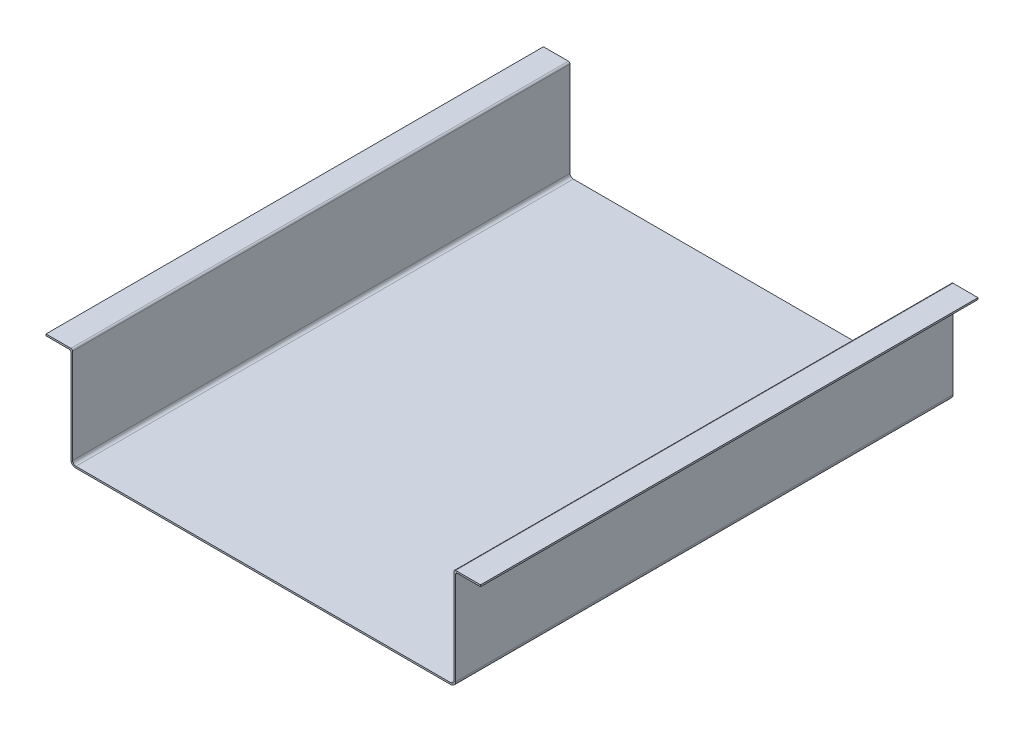
SolidWorks part; units mm, degrees
material "6061-T6 (SS)"
ref_plane "Front Plane" through (0, 0, 0) normal (0, 0, 1) x (1, 0, 0)
ref_plane "Top Plane" through (0, 0, 0) normal (0, 1, 0) x (1, 0, 0)
ref_plane "Right Plane" through (0, 0, 0) normal (1, 0, 0) x (0, 0, -1)
sketch "Sketch2" plane through (0, 0, 0) normal (0, 0, 1) x (1, 0, 0)
  line L0 (-179.1462, 0) -> (179.1462, 0)
  line L1 (-183.896, 4.7498) -> (-183.896, 93.6625)
  line L2 (-185.4835, 95.25) -> (-207.6958, 95.25)
  line L3 (-182.2958, 95.25) -> (-182.2958, 4.7625)
  line L4 (-179.1208, 1.5875) -> (179.1208, 1.5875)
  line L5 (182.2958, 4.7625) -> (182.2958, 95.2627)
  line L6 (185.4835, 95.25) -> (207.6958, 95.25)
  line L7 (183.896, 93.6625) -> (183.896, 4.7498)
  line L8 (0, 1.5875) -> (0, 0) construction
  line L9 (-207.6958, 95.25) -> (-207.6958, 96.8502)
  line L10 (-207.6958, 96.8502) -> (-183.8833, 96.8502)
  line L11 (-182.2958, 95.25) -> (-182.2958, 95.2627)
  line L12 (-182.2958, 94.3244) -> (-183.896, 94.3244) construction
  line L13 (207.6958, 95.25) -> (207.6958, 96.8502)
  line L14 (207.6958, 96.8502) -> (183.8833, 96.8502)
  line L16 (183.896, 90.4071) -> (182.2958, 90.4071) construction
  arc A0 (-182.2958, 4.7625) -> (-179.1208, 1.5875) centre (-179.1208, 4.7625) ccw
  arc A1 (-179.1462, 0) -> (-183.896, 4.7498) centre (-179.1462, 4.7498) cw
  arc A2 (179.1462, 0) -> (183.896, 4.7498) centre (179.1462, 4.7498) ccw
  arc A3 (179.1208, 1.5875) -> (182.2958, 4.7625) centre (179.1208, 4.7625) ccw
  arc A4 (-183.8833, 96.8502) -> (-182.2958, 95.2627) centre (-183.8833, 95.2627) cw
  arc A5 (-183.896, 93.6625) -> (-185.4835, 95.25) centre (-185.4835, 93.6625) ccw
  arc A6 (183.8833, 96.8502) -> (182.2958, 95.2627) centre (183.8833, 95.2627) ccw
  arc A7 (185.4835, 95.25) -> (183.896, 93.6625) centre (185.4835, 93.6625) ccw
  point P3 (0, 0)
  point P16 (-183.896, 0)
  point P19 (183.896, 0)
  point P31 (-183.896, 95.25)
  dimension "D4" = 3.175
  dimension "D5" = 4.7498
  dimension "D6" = 4.7498
  dimension "D7" = 3.175
  dimension "D8" = 1.5875
  dimension "D11" = 1.5875
  dimension "D1" = 95.25
  dimension "D2" = 1.6002
  dimension "D3" = 367.792
  dimension "D9" = 1.6002
  dimension "D10" = 1.6002
  dimension "D12" = 25.4
  dimension "D13" = 25.4
  dimension "D14" = 1.5875
extrude "Boss-Extrude1" add sketch "Sketch2" along normal blind 475.488
